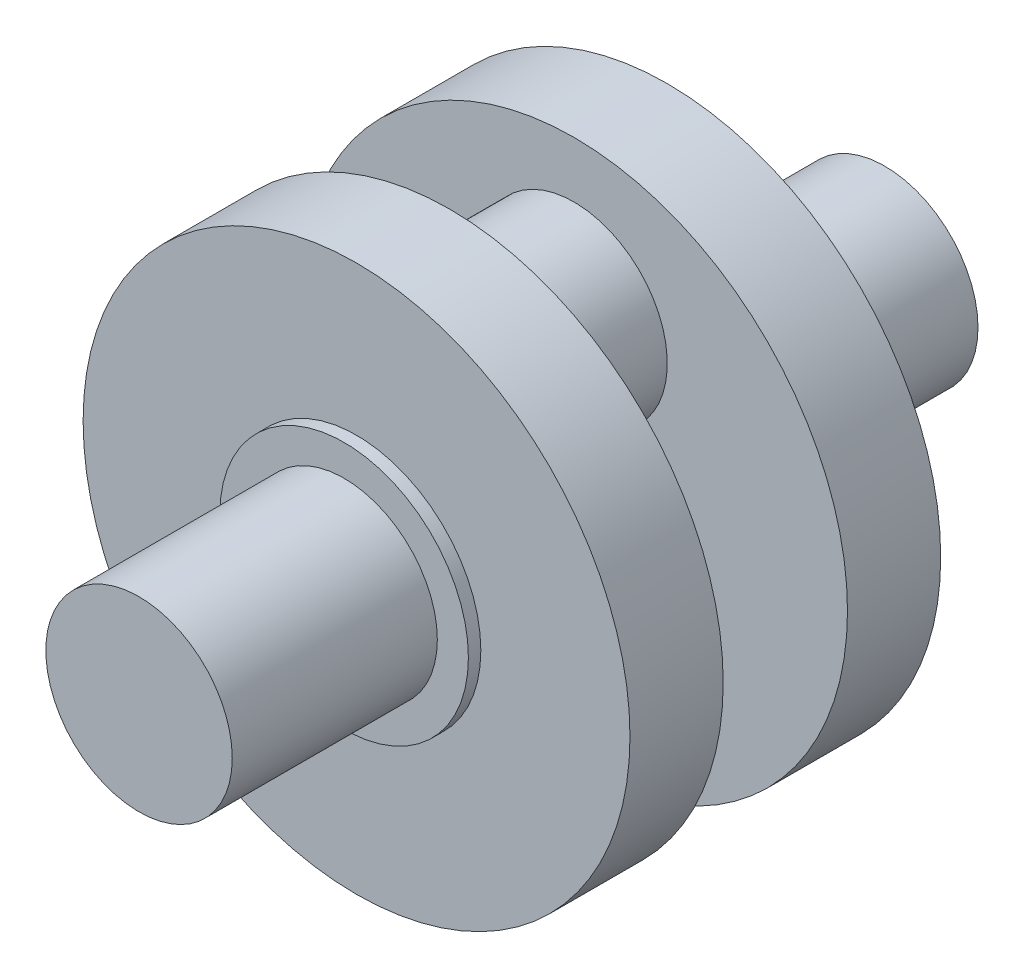
SolidWorks part; units mm, degrees
ref_plane "Płaszczyzna przednia" through (0, 0, 0) normal (0, 0, 1) x (1, 0, 0)
ref_plane "Płaszczyzna górna" through (0, 0, 0) normal (0, 1, 0) x (1, 0, 0)
ref_plane "Płaszczyzna prawa" through (0, 0, 0) normal (1, 0, 0) x (0, 0, -1)
sketch "Szkic2" plane through (0, 0, 0) normal (0, 0, 1) x (1, 0, 0)
  circle A0 centre (0, 0) radius 15
  point P3 (0, 0)
  dimension "D1" = 30
extrude "Dodanie-wyciągnięcie1" add sketch "Szkic2" along normal blind 33
sketch "Szkic3" plane through (0, 0, 0) normal (0, 0, -1) x (-1, 0, 0)
  circle A0 centre (0, 0) radius 20
  dimension "D1" = 40
extrude "Dodanie-wyciągnięcie2" add sketch "Szkic3" along normal blind 2 contours A0
sketch "Szkic4" plane through (0, 0, -2) normal (0, 0, -1) x (-1, 0, 0)
  circle A0 centre (0, 0) radius 44
  dimension "D1" = 88
extrude "Dodanie-wyciągnięcie3" add sketch "Szkic4" along normal blind 15 contours A0
sketch "Szkic5" plane through (0, 0, -17) normal (0, 0, -1) x (-1, 0, 0)
  circle A0 centre (0, 20) radius 15
  point P2 (0, 0)
  dimension "D2" = 30
  dimension "D1" = 20
extrude "Dodanie-wyciągnięcie4" add sketch "Szkic5" along normal blind 10 contours A0
mirror "Lustro14" about plane through (0, 20, -27) normal (0, 0, -1) of "Dodanie-wyciągnięcie4", "Dodanie-wyciągnięcie3", "Dodanie-wyciągnięcie2", "Dodanie-wyciągnięcie1"
